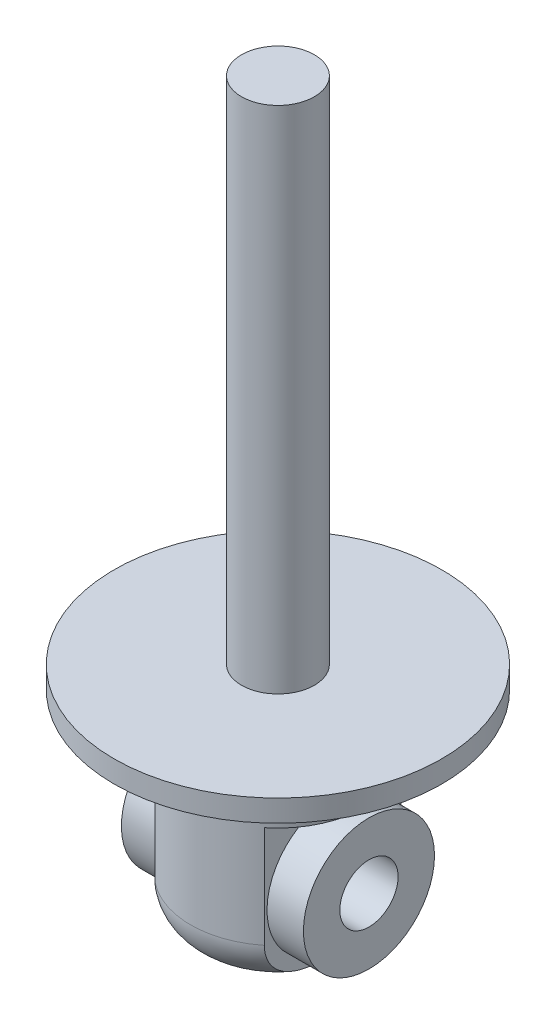
SolidWorks part; units mm, degrees
material "3003 Alloy"
ref_plane "Ebene vorne" through (0, 0, 0) normal (0, 0, 1) x (1, 0, 0)
ref_plane "Ebene oben" through (0, 0, 0) normal (0, 1, 0) x (1, 0, 0)
ref_plane "Ebene rechts" through (0, 0, 0) normal (1, 0, 0) x (0, 0, -1)
sketch "Sketch1" plane through (0, 0, 0) normal (0, 1, 0) x (1, 0, 0)
  circle A0 centre (0, 0) radius 22.5
  point P3 (0, 0)
  dimension "D1" = 45
extrude "Boss-Extrude1" add sketch "Sketch1" along normal blind 3
sketch "Sketch2" plane through (0, 3, 0) normal (0, 1, 0) x (1, 0, 0)
  circle A0 centre (0, 0) radius 5
  dimension "D1" = 10
extrude "Boss-Extrude2" add sketch "Sketch2" along normal blind 70
sketch "Sketch3" plane through (0, 0, 0) normal (0, -1, 0) x (1, 0, 0)
  circle A0 centre (0, 0) radius 12
  dimension "D1" = 24
extrude "Boss-Extrude3" add sketch "Sketch3" along normal blind 28
fillet "Fillet1" radius 6 1 edges at (0, -28, -12)
sketch "Sketch4" plane through (0, 0, 0) normal (0, 0, 1) x (1, 0, 0)
  line L0 (0, 0) -> (0, -28) construction
  line L1 (-6, -28) -> (6, -28) construction
  line L2 (7.5, -8) -> (7.5, -28)
  line L3 (7.5, -28) -> (29.0312, -28)
  line L4 (29.0312, -28) -> (29.0312, -8)
  line L5 (29.0312, -8) -> (7.5, -8)
  line L6 (-29.0312, -8) -> (-7.5, -8)
  line L7 (-29.0312, -28) -> (-29.0312, -8)
  line L8 (-7.5, -28) -> (-29.0312, -28)
  line L9 (-7.5, -8) -> (-7.5, -28)
  dimension "D1" = 20
  dimension "D2" = 7.5
extrude "Cut-Extrude1" cut sketch "Sketch4" against normal through all both and the other way through all
sketch "Sketch5" plane through (7.5, 0, 0) normal (1, 0, 0) x (0, 0, -1)
  line L0 (0, 0) -> (0, -28) construction
  line L1 (-6, -28) -> (6, -28) construction
  circle A0 centre (0, -18) radius 4
  point P7 (0, -16.5631)
  dimension "D1" = 8
  dimension "D2" = 10
extrude "Cut-Extrude2" cut sketch "Sketch5" against normal through all both
sketch "Sketch6" plane through (7.5, 0, 0) normal (1, 0, 0) x (0, 0, -1)
  circle A0 centre (0, -18) radius 9
  circle A1 centre (0, -18) radius 4 construction
  circle A2 centre (0, -18) radius 4
  dimension "D1" = 18
extrude "Boss-Extrude7" add sketch "Sketch6" along normal blind 5
mirror "Mirror1" about plane through (0, 0, 0) normal (1, 0, 0) of "Boss-Extrude7"
equation "\"Hole_DIst_from_Top\"=10"
equation "\"D2@Sketch5\"=\"Hole_DIst_from_Top\""
